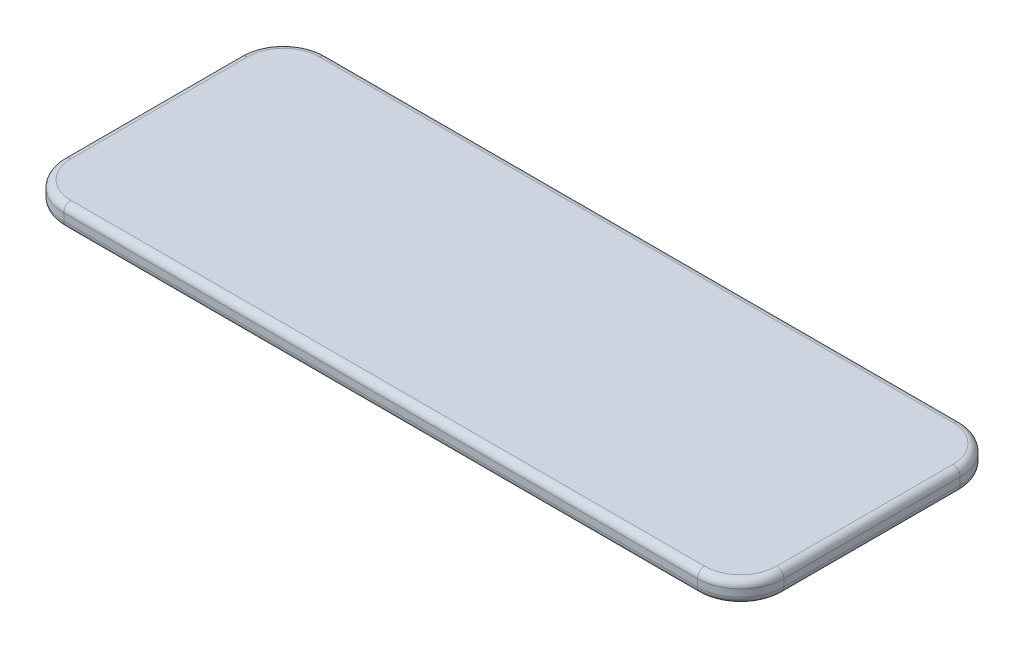
SolidWorks part; units mm, degrees
ref_plane "Front Plane" through (0, 0, 0) normal (0, 0, 1) x (1, 0, 0)
ref_plane "Top Plane" through (0, 0, 0) normal (0, 1, 0) x (1, 0, 0)
ref_plane "Right Plane" through (0, 0, 0) normal (1, 0, 0) x (0, 0, -1)
sketch "Sketch1" plane through (0, 0, 0) normal (0, 1, 0) x (1, 0, 0)
  line L1 (-60, 0) -> (-940, 0)
  line L2 (0, 60) -> (0, 305)
  line L3 (-60, 365) -> (-940, 365)
  line L4 (-1000, 60) -> (-1000, 305)
  arc A0 (0, 305) -> (-60, 365) centre (-60, 305) ccw
  arc A1 (-60, 0) -> (0, 60) centre (-60, 60) ccw
  arc A2 (-940, 0) -> (-1000, 60) centre (-940, 60) cw
  arc A3 (-940, 365) -> (-1000, 305) centre (-940, 305) ccw
  point P7 (0, 365)
  point P10 (0, 0)
  point P15 (-1000, 365)
  dimension "D3" = 60
  dimension "D1" = 1000
  dimension "D2" = 365
extrude "Boss-Extrude1" add sketch "Sketch1" along normal blind 30
fillet "Fillet1" radius 10 16 edges at (-982.4264, 0, -347.4264) (-500, 0, -365) (-17.5736, 0, -347.4264) (0, 0, -182.5) (-17.5736, 0, -17.5736) (-500, 0, 0) (-982.4264, 0, -17.5736) (-982.4264, 30, -17.5736) (-1000, 30, -182.5) (-982.4264, 30, -347.4264) (-500, 30, -365) (-17.5736, 30, -347.4264) (0, 30, -182.5) (-17.5736, 30, -17.5736) (-1000, 0, -182.5) (-500, 30, 0)
